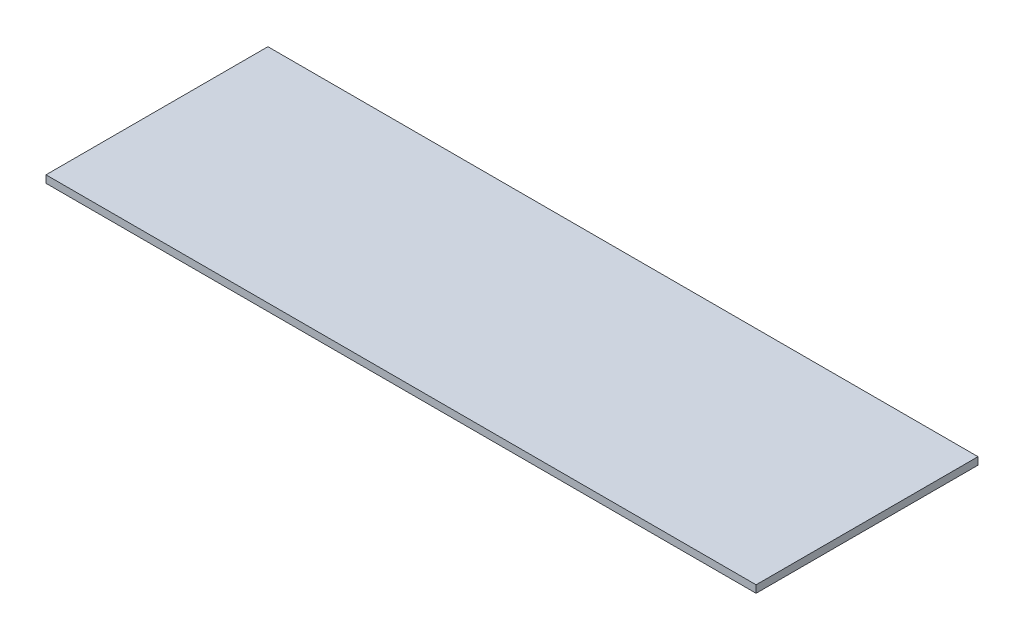
SolidWorks part; units mm, degrees
ref_plane "Front Plane" through (0, 0, 0) normal (0, 0, 1) x (1, 0, 0)
ref_plane "Top Plane" through (0, 0, 0) normal (0, 1, 0) x (1, 0, 0)
ref_plane "Right Plane" through (0, 0, 0) normal (1, 0, 0) x (0, 0, -1)
sketch "Sketch2" plane through (0, 0, 0) normal (0, 1, 0) x (1, 0, 0)
  line L1 (0, 0) -> (266.7, 0)
  line L2 (0, 0) -> (0, 76.2)
  line L3 (0, 76.2) -> (266.7, 76.2)
  line L4 (266.7, 0) -> (266.7, 76.2)
  dimension "D1" = 266.7
  dimension "D2" = 76.2
extrude "Boss-Extrude2" add sketch "Sketch2" along normal blind 2.54
sketch "Sketch3" plane through (0, 0, 0) normal (-1, 0, 0) x (0, 0, 1)
  line L1 (-78.4669, 37.1709) -> (27.5774, 37.1709)
  line L2 (-78.4669, 37.1709) -> (-78.4669, -30.1957)
  line L3 (-78.4669, -30.1957) -> (27.5774, -30.1957)
  line L4 (27.5774, 37.1709) -> (27.5774, -30.1957)
extrude "Cut-Extrude1" cut sketch "Sketch3" against normal blind 19.05
sketch "Sketch4" plane through (19.05, 0, 0) normal (-1, 0, 0) x (0, 0, 1)
  line L1 (-92.4885, 12.702) -> (8.1667, 12.702)
  line L2 (-92.4885, 12.702) -> (-92.4885, -14.5963)
  line L3 (-92.4885, -14.5963) -> (8.1667, -14.5963)
  line L4 (8.1667, 12.702) -> (8.1667, -14.5963)
extrude "Cut-Extrude2" cut sketch "Sketch4" against normal blind 3.81
